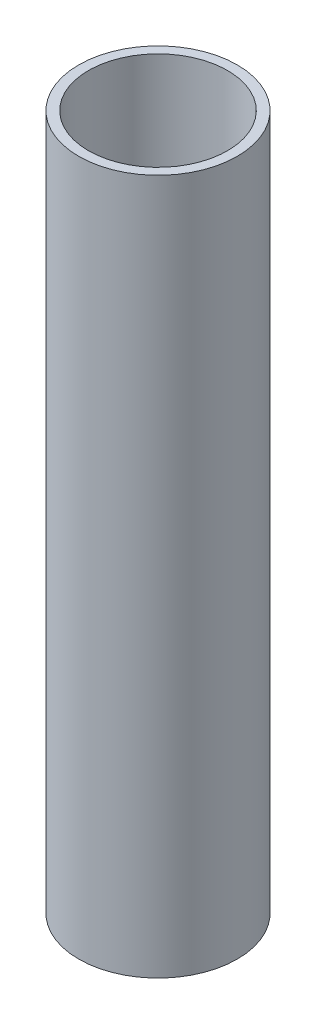
SolidWorks part; units mm, degrees
material "AISI 316 Stainless Steel Sheet (SS)"
ref_plane "Front Plane" through (0, 0, 0) normal (0, 0, 1) x (1, 0, 0)
ref_plane "Top Plane" through (0, 0, 0) normal (0, 1, 0) x (1, 0, 0)
ref_plane "Right Plane" through (0, 0, 0) normal (1, 0, 0) x (0, 0, -1)
sketch "Sketch1" plane through (0, 0, 0) normal (0, 1, 0) x (1, 0, 0)
  circle A0 centre (0, 0) radius 14.478
  circle A1 centre (0, 0) radius 12.7
  dimension "D1" = 25.4
  dimension "D2" = 28.956
extrude "Boss-Extrude1" add sketch "Sketch1" along normal blind 127
